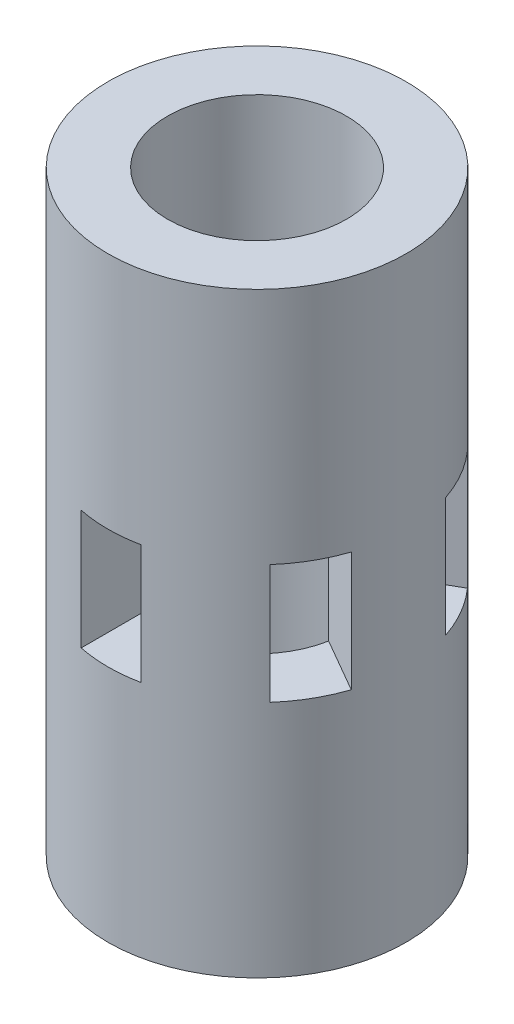
SolidWorks part; units mm, degrees
ref_plane "Front Plane" through (0, 0, 0) normal (0, 0, 1) x (1, 0, 0)
ref_plane "Top Plane" through (0, 0, 0) normal (0, 1, 0) x (1, 0, 0)
ref_plane "Right Plane" through (0, 0, 0) normal (1, 0, 0) x (0, 0, -1)
sketch "Sketch1" plane through (0, 0, 0) normal (0, 0, 1) x (1, 0, 0)
  line L0 (0, 56.4516) -> (0, -56.2903) construction
  line L2 (-15, -50) -> (-25, -50)
  line L3 (-15, -50) -> (-15, 50)
  line L4 (-15, 50) -> (-25, 50)
  line L5 (-25, -50) -> (-25, 50)
  line L6 (-15, -50) -> (-25, 50) construction
  line L7 (-15, 50) -> (-25, -50) construction
  point P1 (-20, 0)
  dimension "D1" = 10
  dimension "D2" = 100
  dimension "D3" = 20
revolve "Revolve1" add sketch "Sketch1" angle 360 about L0
sketch "Sketch2" plane through (0, 0, 0) normal (0, 0, 1) x (1, 0, 0)
  line L1 (5, 10) -> (-5, 10)
  line L2 (5, 10) -> (5, -10)
  line L3 (5, -10) -> (-5, -10)
  line L4 (-5, 10) -> (-5, -10)
  line L5 (5, 10) -> (-5, -10) construction
  line L6 (5, -10) -> (-5, 10) construction
  point P0 (0, 0)
  dimension "D1" = 10
  dimension "D2" = 20
extrude "Cut-Extrude1" cut sketch "Sketch2" against normal offset from surface (40.4949 mm away) 16
pattern_circular "CirPattern1" count 6 over 360 about axis through (0, 0, 0) along (0, 1, 0) of "Cut-Extrude1"
